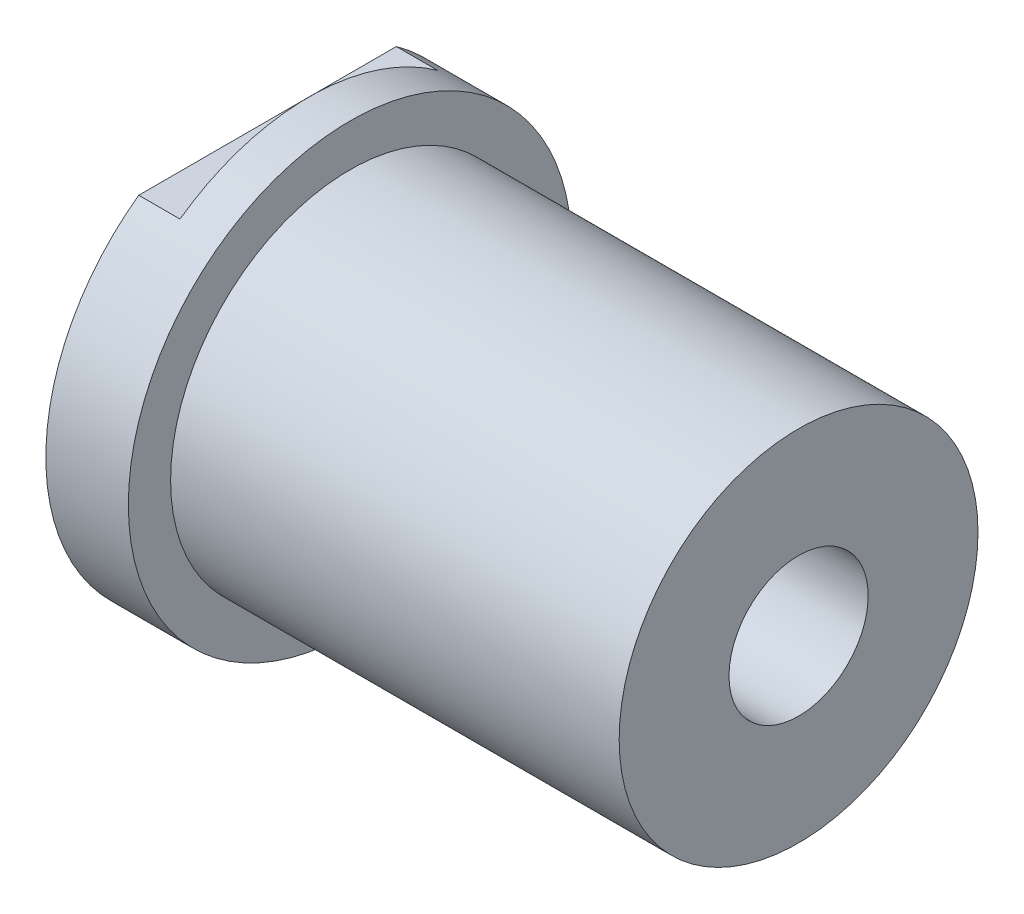
SolidWorks part; units mm, degrees
ref_plane "Plan de face" through (0, 0, 0) normal (0, 0, 1) x (1, 0, 0)
ref_plane "Plan de dessus" through (0, 0, 0) normal (0, 1, 0) x (1, 0, 0)
ref_plane "Plan de droite" through (0, 0, 0) normal (1, 0, 0) x (0, 0, -1)
sketch "Esquisse2" plane through (0, 0, 0) normal (0, 0, 1) x (1, 0, 0)
  line L0 (0, 0) -> (0, 43)
  line L1 (0, 43) -> (103, 43)
  line L2 (103, 43) -> (103, 0)
  line L3 (103, 0) -> (0, 0)
  dimension "D1" = 103
  dimension "D2" = 43
revolve "Révolution1" add sketch "Esquisse2" angle 360 about L3
sketch "Esquisse3" plane through (103, 0, 0) normal (1, 0, 0) x (0, 0, -1)
  circle A0 centre (0, 0) radius 34.8
  dimension "D1" = 69.6
extrude "Enlèv. mat.-Extru.1" cut sketch "Esquisse3" against normal blind 87 flip side to cut
sketch "Esquisse4" plane through (0, 0, 0) normal (-1, 0, 0) x (0, 0, 1)
  line L1 (-24.98, 35) -> (24.98, 35)
  circle A0 centre (0, 0) radius 43 construction
extrude "Enlèv. mat.-Extru.2" cut sketch "Esquisse4" against normal blind 8 and the other way through all
sketch "Esquisse5" plane through (0, 0, 0) normal (-1, 0, 0) x (0, 0, 1)
  line L1 (-24.98, -35) -> (24.98, -35)
  arc A0 (-24.98, 35) -> (24.98, 35) centre (0, 0) ccw construction
extrude "Enlèv. mat.-Extru.3" cut sketch "Esquisse5" against normal blind 8 and the other way through all flip side to cut
sketch "Esquisse7" plane through (0, 0, 0) normal (-1, 0, 0) x (0, 0, 1)
  circle A0 centre (0, 0) radius 19.5
  dimension "D1" = 39
extrude "Enlèv. mat.-Extru.4" cut sketch "Esquisse7" against normal blind 24
sketch "Esquisse8" plane through (24, 0, 0) normal (-1, 0, 0) x (0, 0, 1)
  circle A0 centre (0, 0) radius 13.5
  dimension "D1" = 27
extrude "Enlèv. mat.-Extru.5" cut sketch "Esquisse8" against normal through all
